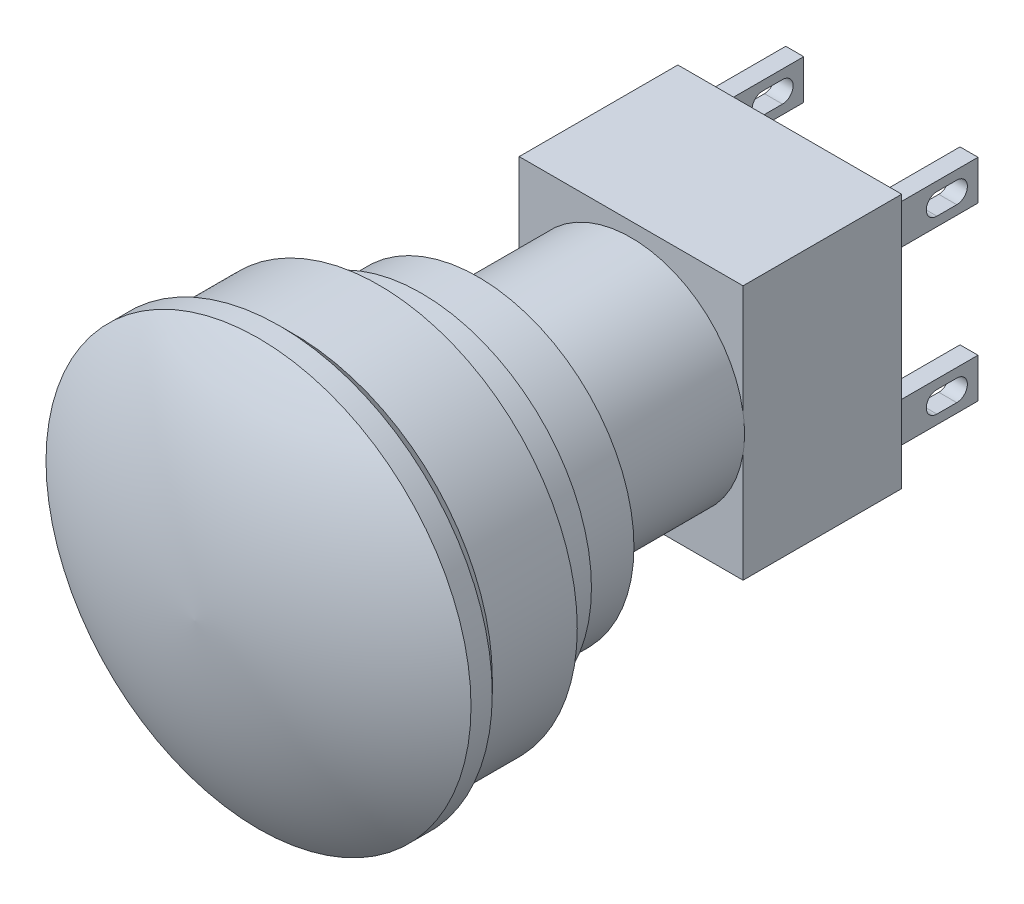
SolidWorks part; units mm, degrees
ref_plane "Front Plane" through (0, 0, 0) normal (0, 0, 1) x (1, 0, 0)
ref_plane "Top Plane" through (0, 0, 0) normal (0, 1, 0) x (1, 0, 0)
ref_plane "Right Plane" through (0, 0, 0) normal (1, 0, 0) x (0, 0, -1)
sketch "Sketch1" plane through (0, 0, 0) normal (1, 0, 0) x (0, 0, -1)
  line L0 (0, 15) -> (1.5, 15)
  line L1 (1.5, 15) -> (2.5, 14)
  line L2 (2.5, 14) -> (8.5, 14)
  line L3 (8.5, 14) -> (9.5, 12)
  line L4 (9.5, 12) -> (11.5, 12)
  line L5 (11.5, 12) -> (11.5, 11)
  line L6 (11.5, 11) -> (15.5, 11)
  line L7 (15.5, 11) -> (15.5, 8)
  line L8 (15.5, 8) -> (26.3, 8)
  line L9 (0, 0) -> (50000, 0) construction
  line L10 (26.3, 8) -> (26.3, 0)
  line L11 (26.3, 0) -> (-4.5, 0)
  spline S0 degree 3 poles (-4.5, 0) (-4.3004, 5.2552) (-2.9773, 10.6042) (0, 15) knots 0 0 0 0 1 1 1 1
  dimension "D1" = 30
  dimension "D2" = 20
  dimension "D3" = 1.5
  dimension "D4" = 6
  dimension "D5" = 1
  dimension "D6" = 1
  dimension "D7" = 2
  dimension "D8" = 1
  dimension "D9" = 2
  dimension "D10" = 1
  dimension "D11" = 4
  dimension "D12" = 16
  dimension "D13" = 10.8
revolve "Revolve1" add sketch "Sketch1" angle 360 about L9
sketch "Sketch2" plane through (0, 0, -26.3) normal (0, 0, -1) x (-1, 0, 0)
  line L1 (-7.9, 9) -> (7.9, 9)
  line L2 (-7.9, 9) -> (-7.9, -9)
  line L3 (-7.9, -9) -> (7.9, -9)
  line L4 (7.9, 9) -> (7.9, -9)
  line L5 (-7.9, 9) -> (7.9, -9) construction
  line L6 (-7.9, -9) -> (7.9, 9) construction
  point P0 (0, 0)
  dimension "D1" = 18
  dimension "D2" = 15.8
extrude "Boss-Extrude2" add sketch "Sketch2" along normal blind 11.2
sketch "Sketch3" plane through (0, 9, 0) normal (0, 1, 0) x (1, 0, 0)
  line L0 (-7.9, 37.5) -> (7.9, 37.5) construction
  line L1 (-6.785, 44) -> (-5.515, 44)
  line L2 (-6.785, 44) -> (-6.785, 37.5)
  line L3 (-6.785, 37.5) -> (-5.515, 37.5)
  line L4 (-5.515, 44) -> (-5.515, 37.5)
  line L5 (-6.785, 44) -> (-5.515, 37.5) construction
  line L6 (-6.785, 37.5) -> (-5.515, 44) construction
  line L7 (-6.15, 40.75) -> (6.15, 40.75) construction
  line L8 (5.515, 44) -> (6.785, 44)
  line L9 (5.515, 44) -> (5.515, 37.5)
  line L10 (5.515, 37.5) -> (6.785, 37.5)
  line L11 (6.785, 44) -> (6.785, 37.5)
  line L12 (5.515, 44) -> (6.785, 37.5) construction
  line L13 (5.515, 37.5) -> (6.785, 44) construction
  line L14 (8, 15.5) -> (-8, 15.5) construction
  point P0 (-6.15, 40.75)
  point P7 (6.15, 40.75)
  point P14 (0, 40.75)
  dimension "D1" = 12.3
  dimension "D2" = 28.5
  dimension "D3" = 1.27
extrude "Boss-Extrude3" add sketch "Sketch3" against normal up to surface (18 mm away) up to face at (0, -9, -31.9)
sketch "Sketch4" plane through (6.785, 0, 0) normal (1, 0, 0) x (0, 0, -1)
  line L0 (37.5, 9) -> (37.5, -9) construction
  line L1 (44, 7.45) -> (37.5, 7.45)
  line L2 (44, 7.45) -> (44, 4.65)
  line L3 (44, 4.65) -> (37.5, 4.65)
  line L4 (37.5, 7.45) -> (37.5, 4.65)
  line L5 (44, 7.45) -> (37.5, 4.65) construction
  line L6 (44, 4.65) -> (37.5, 7.45) construction
  line L7 (44, -9) -> (44, 9) construction
  line L8 (44, -7.45) -> (37.5, -7.45)
  line L9 (44, -7.45) -> (44, -4.65)
  line L10 (44, -4.65) -> (37.5, -4.65)
  line L11 (37.5, -7.45) -> (37.5, -4.65)
  line L12 (44, -7.45) -> (37.5, -4.65) construction
  line L13 (44, -4.65) -> (37.5, -7.45) construction
  line L14 (40.75, 6.05) -> (40.75, -6.05) construction
  line L15 (37.5, 7.45) -> (37.5, 9)
  line L16 (37.5, 9) -> (44, 9)
  line L17 (44, 9) -> (44, 7.45)
  line L18 (44, 4.65) -> (44, -4.65)
  line L19 (37.5, 4.65) -> (37.5, -4.65)
  line L20 (37.5, -7.45) -> (37.5, -9)
  line L21 (37.5, -9) -> (44, -9)
  line L22 (44, -9) -> (44, -7.45)
  point P0 (40.75, 6.05)
  point P7 (40.75, -6.05)
  point P16 (40.75, 0)
  line M1 (37.5, -9) -> (44, -9)
  line M2 (44, -9) -> (44, 9)
  line M3 (44, 9) -> (37.5, 9)
  line M4 (37.5, 9) -> (37.5, -9)
  dimension "D1" = 12.1
  dimension "D2" = 2.8
extrude "Cut-Extrude1" cut sketch "Sketch4" against normal through all contours L1 M2 M3 M4 | L10 L3 M2 M4 | L8 M2 M4 M1
sketch "Sketch5" plane through (6.785, 0, 0) normal (1, 0, 0) x (0, 0, -1)
  line L0 (41.1, 6.05) -> (42.5, 6.05) construction
  line L1 (41.1, 6.8) -> (42.5, 6.8)
  line L2 (41.1, 5.3) -> (42.5, 5.3)
  line L3 (44, 7.45) -> (44, 4.65) construction
  arc A0 (41.1, 6.8) -> (41.1, 5.3) centre (41.1, 6.05) ccw
  arc A1 (42.5, 5.3) -> (42.5, 6.8) centre (42.5, 6.05) ccw
  point P2 (41.8, 6.05)
  point P9 (44, 6.05)
  dimension "D3" = 0.75
  dimension "D1" = 1.4
  dimension "D2" = 1.5
extrude "Cut-Extrude2" cut sketch "Sketch5" against normal through all
mirror "Mirror1" about plane through (0, 0, 0) normal (0, 1, 0) of "Cut-Extrude2"
